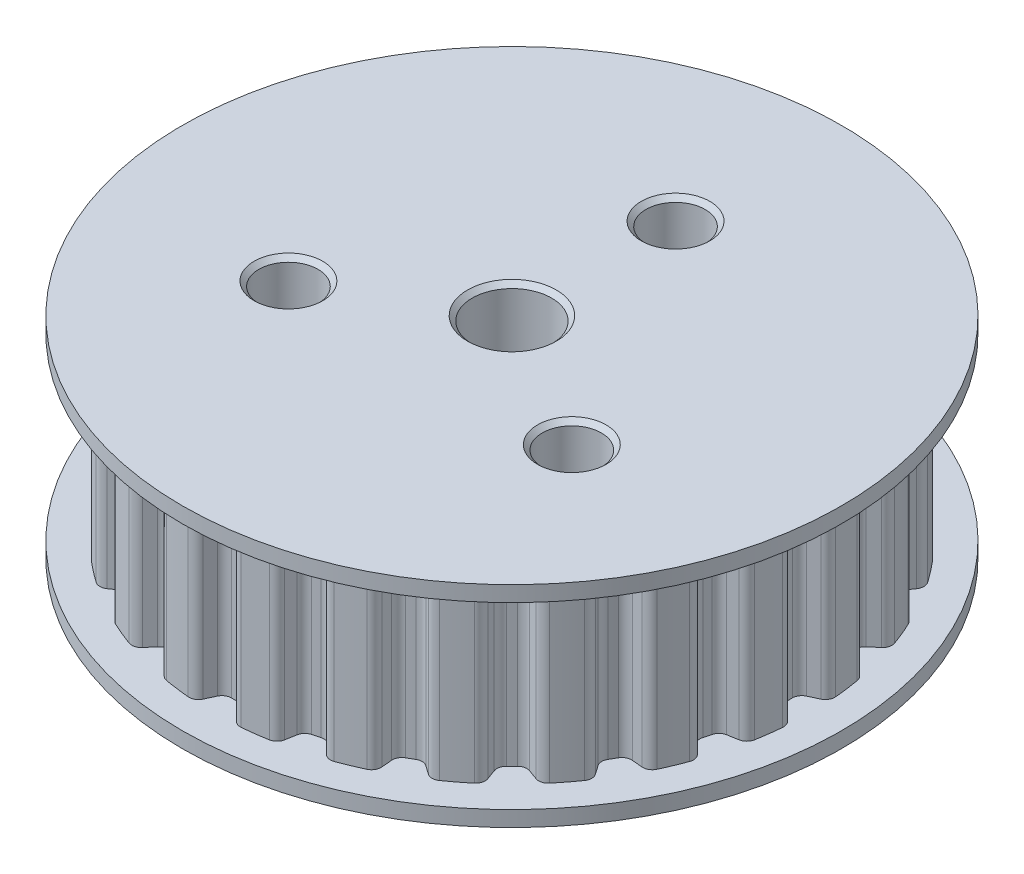
SolidWorks part; units mm, degrees
material "Nylon 101"
ref_plane "Front Plane" through (0, 0, 0) normal (0, 0, 1) x (1, 0, 0)
ref_plane "Top Plane" through (0, 0, 0) normal (0, 1, 0) x (1, 0, 0)
ref_plane "Right Plane" through (0, 0, 0) normal (1, 0, 0) x (0, 0, -1)
sketch "Sketch1" plane through (0, 0, 0) normal (0, 1, 0) x (1, 0, 0)
  circle A0 centre (0, 0) radius 17.75
  circle A1 centre (0, 0) radius 19.15
  circle A2 centre (0, 0) radius 19.4042
  dimension "D1" = 35.5
  dimension "D2" = 38.3
  dimension "D3" = 38.8083
sketch "Sketch2" plane through (0, 0, 0) normal (0, 1, 0) x (1, 0, 0)
  line L0 (0, 0) -> (0, 17.75) construction
  line L1 (0, 17.75) -> (0, 19.15) construction
  line L2 (0, 19.15) -> (0, 19.4042) construction
  line L3 (0, 0) -> (2.3168, 17.5981) construction
  line L4 (2.3168, 17.5981) -> (2.4996, 18.9862) construction
  line L5 (2.4996, 18.9862) -> (2.5328, 19.2382) construction
  line L6 (-1.2732, 19.1076) -> (-0.6349, 17.7386)
  line L7 (1.2732, 19.1076) -> (0.6349, 17.7386)
  line L8 (3.7156, 18.7861) -> (3.9779, 17.2985)
  arc A0 (2.5328, 19.2382) -> (0, 19.4042) centre (0, 0) ccw construction
  arc A1 (3.7156, 18.7861) -> (1.2732, 19.1076) centre (0, 0) ccw
  arc A2 (3.9779, 17.2985) -> (0.6349, 17.7386) centre (0, 0) ccw
  circle A3 centre (0, 0) radius 17.75 construction
  circle A4 centre (0, 0) radius 19.15 construction
  circle A5 centre (0, 0) radius 19.4042 construction
  dimension "D3" = 25
  dimension "D1" = 2.54
  dimension "D2" = 1.27
sketch "Sketch3" plane through (0, 0, 0) normal (0, 1, 0) x (1, 0, 0)
  circle A0 centre (0, 0) radius 17.75 construction
  circle A1 centre (0, 0) radius 17.75
extrude "Boss-Extrude1" add sketch "Sketch3" along normal mid plane 11.5
extrude "Boss-Extrude2" add sketch "Sketch2" along normal mid plane 11.5 contours A2 L8 A1 L7
fillet "Fillet1" radius 0.61 2 edges at (3.9779, 0, -17.2985) (0.6349, 0, -17.7386)
fillet "Fillet2" radius 0.61 2 edges at (3.7156, 0, -18.7861) (1.2732, 0, -19.1076)
pattern_circular "CirPattern1" count 24 over 360 about axis through (0, 0, 0) along (0, 1, 0) of "Boss-Extrude2", "Fillet2", "Fillet1"
sketch "Sketch4" plane through (0, 5.75, 0) normal (0, 1, 0) x (1, 0, 0)
  circle A0 centre (0, 0) radius 21.15
  arc A2 (3.7156, 18.7861) -> (1.2732, 19.1076) centre (0, 0) ccw construction
  dimension "D1" = 2
extrude "Boss-Extrude3" add sketch "Sketch4" along normal blind 1
mirror "Mirror1" about plane through (0, 0, 0) normal (0, 1, 0) of "Boss-Extrude3"
sketch "Sketch5" plane through (0, 6.75, 0) normal (0, 1, 0) x (1, 0, 0)
  line L1 (0, 10.5) -> (0, 0) construction
  circle A0 centre (0, 0) radius 2.55
  circle A1 centre (0, 10.5) radius 1.9
  circle A7 centre (9.0933, -5.25) radius 1.9
  circle A8 centre (-9.0933, -5.25) radius 1.9
  point P14 (0, 0)
  dimension "D1" = 5.1
  dimension "D2" = 3.8
  dimension "D3" = 10.5
  dimension "D4" = 3
extrude "Cut-Extrude1" cut sketch "Sketch5" against normal through all both and the other way through all
chamfer "Chamfer2" distance 0.3 angle 45 8 edges at (0, -6.75, -8.6) (0, -6.75, 2.55) (0, 6.75, -8.6) (0, 6.75, 2.55) (9.0933, -6.75, 7.15) (9.0933, 6.75, 7.15) (-9.0933, -6.75, 7.15) (-9.0933, 6.75, 7.15)
sketch "Sketch6" plane through (0, -6.75, 0) normal (0, -1, 0) x (1, 0, 0)
  circle A0 centre (0, 0) radius 15
  dimension "D1" = 30
extrude "Cut-Extrude2" cut sketch "Sketch6" against normal blind 3.4
equation "\"p\"= 5.08'Pitch - Type: L100"
equation "\"td\"= 1.4'Tooth depth"
equation "\"alpha\"= 25'Tooth angle in degrees"
equation "\"z\"= 24'Number of teeth"
equation "\"s\"= 1.27'Tooth width"
equation "\"rt\"= 0.61'Tooth top fillet"
equation "\"rb\"= 0.61'Tooth bottom fillet"
equation "\"w\"= 11.5'Pulley width"
equation "\"pd\"= \"p\" * \"D1@CirPattern1\" / pi'Pitch diameter"
equation "\"od\"= 38.3'Outside diameter"
equation "\"fd\"= \"D2@Sketch1\" - 2 * \"td\"'Foot diameter"
equation "\"D1@Sketch1\"=\"fd\""
equation "\"D3@Sketch1\"= \"pd\""
equation "\"D3@Sketch2\"= \"alpha\""
equation "\"D1@Sketch2\"= \"p\" / 2"
equation "\"D2@Sketch2\"= \"s\""
equation "\"D1@Boss-Extrude1\"= \"w\""
equation "\"D1@Boss-Extrude2\"= \"w\""
equation "\"D1@Fillet1\"= \"rb\""
equation "\"D1@Fillet2\"= \"rt\""
